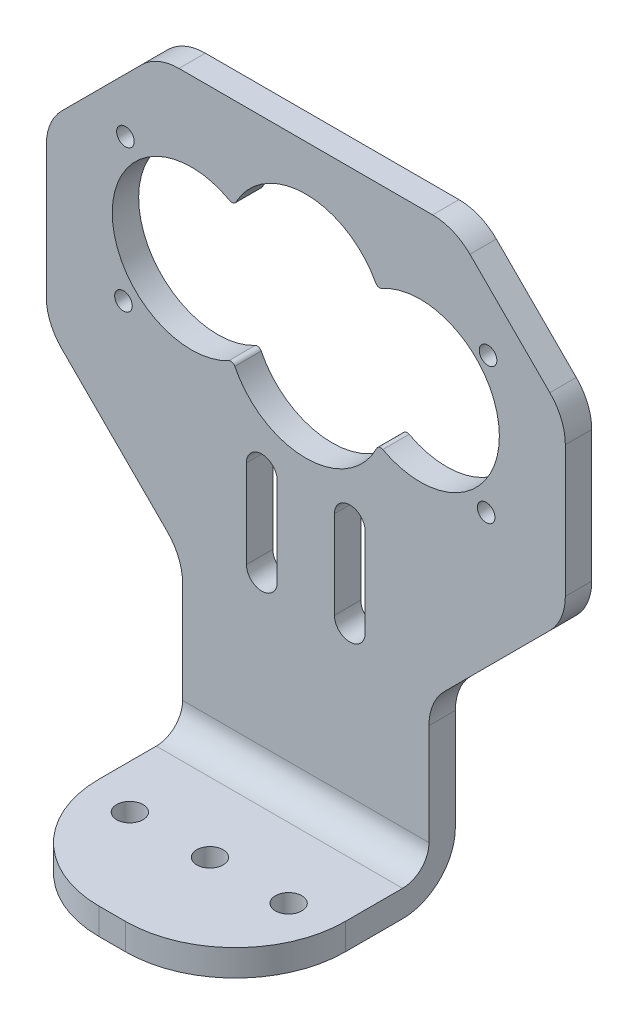
SolidWorks part; units mm, degrees
ref_plane "Front Plane" through (0, 0, 0) normal (0, 0, 1) x (1, 0, 0)
ref_plane "Top Plane" through (0, 0, 0) normal (0, 1, 0) x (1, 0, 0)
ref_plane "Right Plane" through (0, 0, 0) normal (1, 0, 0) x (0, 0, -1)
sketch "Sketch1" plane through (0, 0, 0) normal (0, 1, 0) x (1, 0, 0)
  line L1 (-14, -12.5) -> (14, -12.5)
  line L2 (-14, -12.5) -> (-14, 12.5)
  line L3 (-14, 12.5) -> (14, 12.5)
  line L4 (14, -12.5) -> (14, 12.5)
  line L5 (-14, -12.5) -> (14, 12.5) construction
  line L6 (-14, 12.5) -> (14, -12.5) construction
  point P0 (0, 0)
  dimension "D1" = 25
  dimension "D2" = 28
extrude "Boss-Extrude1" add sketch "Sketch1" along normal blind 3
fillet "Fillet1" radius 12.5 2 edges at (14, 1.5, 12.5) (-14, 1.5, 12.5)
sketch "Sketch2" plane through (0, 3, 0) normal (0, 1, 0) x (1, 0, 0)
  line L0 (14, 0) -> (14, 12.5) construction
  line L1 (-14, 12.5) -> (14, 12.5)
  line L2 (-14, 12.5) -> (-14, 9.5)
  line L3 (-14, 9.5) -> (14, 9.5)
  line L4 (14, 12.5) -> (14, 9.5)
  dimension "D1" = 3
extrude "Boss-Extrude2" add sketch "Sketch2" along normal blind 65
sketch "Sketch3" plane through (14, 0, 0) normal (1, 0, 0) x (0, 0, -1)
  line L0 (9.5, 68) -> (9.5, 3) construction
  line L1 (12.5, 68) -> (9.5, 68)
  line L2 (12.5, 68) -> (12.5, 20)
  line L3 (12.5, 20) -> (9.5, 20)
  line L4 (9.5, 68) -> (9.5, 20)
  line L5 (0, 0) -> (12.5, 0) construction
  dimension "D1" = 20
extrude "Boss-Extrude3" add sketch "Sketch3" along normal blind 15.5
sketch "Sketch4" plane through (-14, 0, 0) normal (-1, 0, 0) x (0, 0, 1)
  line L0 (-12.5, 68) -> (-12.5, 0) construction
  line L1 (-9.5, 68) -> (-12.5, 68)
  line L2 (-9.5, 68) -> (-9.5, 20)
  line L3 (-9.5, 20) -> (-12.5, 20)
  line L4 (-12.5, 68) -> (-12.5, 20)
  line L5 (-12.5, 0) -> (0, 0) construction
  dimension "D1" = 20
extrude "Boss-Extrude4" add sketch "Sketch4" along normal blind 15.5
sketch "Sketch6" plane through (0, 0, -9.5) normal (0, 0, 1) x (1, 0, 0)
  line L0 (-29.5, 20) -> (-29.5, 68) construction
  line L2 (-14, 3) -> (14, 3) construction
  circle A0 centre (-13, 50) radius 9
  circle A1 centre (13, 50) radius 9
  dimension "D1" = 26
  dimension "D2" = 16.5
  dimension "D3" = 47
sketch "Sketch9" plane through (0, 0, -9.5) normal (0, 0, 1) x (1, 0, 0)
  line L1 (-6.9645, 53.248) -> (7.7768, 53.248)
  line L2 (-6.9645, 53.248) -> (-6.9645, 46.5823)
  line L3 (-6.9645, 46.5823) -> (7.7768, 46.5823)
  line L4 (7.7768, 53.248) -> (7.7768, 46.5823)
extrude "Cut-Extrude1" cut sketch "Sketch9" against normal blind 3 contours L1 L4 L3 L2
extrude "Cut-Extrude2" cut sketch "Sketch6" against normal blind 3 contours A1 | A0
sketch "Sketch10" plane through (0, 0, -9.5) normal (0, 0, 1) x (1, 0, 0)
  line L0 (-4.6065, 53.248) -> (4.6065, 53.248) construction
  line L1 (-4.6742, 46.5823) -> (4.6742, 46.5823) construction
  circle A0 centre (-0.0001, 53.8423) radius 9
  circle A1 centre (-0.0008, 45.8423) radius 9
  line M1 (4.6742, 46.5823) -> (-4.6742, 46.5823)
  arc M2 (-4.6742, 46.5823) -> (-4.6065, 53.248) centre (-13, 50) cw
  line M3 (-4.6065, 53.248) -> (4.6065, 53.248)
  arc M4 (4.6065, 53.248) -> (4.6742, 46.5823) centre (13, 50) cw
  dimension "D1" = 8
extrude "Cut-Extrude4" cut sketch "Sketch10" against normal blind 3 contours A1 A0 M4 M2 | A1 A0 M2 M4 | A0 M2 M4 M1 | A1 M4 M2 M3
sketch "Sketch11" plane through (0, 0, -9.5) normal (0, 0, 1) x (1, 0, 0)
  line L0 (-29.5, 55.4) -> (-16.9, 68)
  line L1 (-29.5, 20) -> (-29.5, 68) construction
  line L2 (-29.5, 68) -> (29.5, 68) construction
  line L3 (-16.9, 68) -> (-29.5, 68)
  line L4 (-29.5, 68) -> (-29.5, 55.4)
  line L5 (29.5, 55.4) -> (29.5, 68)
  line L6 (29.5, 68) -> (29.5, 20) construction
  line L7 (29.5, 68) -> (16.9, 68)
  line L8 (16.9, 68) -> (29.5, 55.4)
  line L9 (14, 20) -> (29.5, 20)
  line L10 (29.5, 20) -> (29.5, 35.5)
  line L11 (29.5, 35.5) -> (14, 20)
  line L12 (-14, 20) -> (-29.5, 20)
  line L13 (-29.5, 20) -> (-29.5, 35.5)
  line L14 (-29.5, 35.5) -> (-14, 20)
  dimension "D1" = 12.6
  dimension "D2" = 12.6
  dimension "D3" = 12.6
  dimension "D4" = 12.6
  dimension "D5" = 15.5
  dimension "D6" = 15.5
  dimension "D7" = 15.5
extrude "Cut-Extrude5" cut sketch "Sketch11" against normal blind 3
sketch "Sketch12" plane through (0, 0, -9.5) normal (0, 0, 1) x (1, 0, 0)
  line L0 (-5, 33) -> (-5, 23) construction
  line L1 (-3.25, 33) -> (-3.25, 23)
  line L2 (-6.75, 33) -> (-6.75, 23)
  line L3 (5, 33) -> (5, 23) construction
  line L4 (6.75, 33) -> (6.75, 23)
  line L5 (3.25, 33) -> (3.25, 23)
  line L6 (-14, 20) -> (-14, 3) construction
  line L7 (14, 20) -> (14, 3) construction
  arc A0 (-3.25, 33) -> (-6.75, 33) centre (-5, 33) ccw
  arc A1 (-6.75, 23) -> (-3.25, 23) centre (-5, 23) ccw
  arc A2 (6.75, 33) -> (3.25, 33) centre (5, 33) ccw
  arc A3 (3.25, 23) -> (6.75, 23) centre (5, 23) ccw
  point P2 (-5, 28)
  point P7 (5, 28)
  dimension "D1" = 9
  dimension "D3" = 3
  dimension "D4" = 3
  dimension "D2" = 9
extrude "Cut-Extrude8" cut sketch "Sketch12" against normal blind 3
fillet "Fillet3" radius 3 1 edges
fillet "Fillet4" radius 6 1 edges at (0, 0, -12.5)
fillet "Fillet5" radius 6 2 edges at (-14, 20, -11) (14, 20, -11)
fillet "Fillet6" radius 6 6 edges at (-29.5, 35.5, -11) (-29.5, 55.4, -11) (-16.9, 68, -11) (16.9, 68, -11) (29.5, 55.4, -11) (29.5, 35.5, -11)
fillet "Fillet7" radius 0.5 4 edges at (-8.2881, 42.332, -11) (8.2867, 42.3329, -11) (-8.1783, 57.5994, -11) (8.1782, 57.5994, -11)
sketch "Sketch13" plane through (0, 3, 0) normal (0, 1, 0) x (1, 0, 0)
  circle A0 centre (0, -1.3965) radius 1.5
  circle A1 centre (8.9998, -1.4507) radius 1.5
  circle A2 centre (-8.9994, -1.5) radius 1.5
  dimension "D1" = 9
  dimension "D2" = 9
extrude "Cut-Extrude10" cut sketch "Sketch13" against normal blind 3
sketch "Sketch14" plane through (0, 0, -9.5) normal (0, 0, 1) x (1, 0, 0)
  line L0 (-17.9697, 50.0686) -> (-25.8192, 50.177)
  circle A0 centre (20.5, 41.75) radius 1
  circle A1 centre (-20.5, 58.25) radius 1
  circle A2 centre (-20.7249, 41.9602) radius 1
  circle A3 centre (20.715, 57.3219) radius 1
extrude "Cut-Extrude11" cut sketch "Sketch14" against normal blind 3 contours A1 | A2 | A0 | A3
